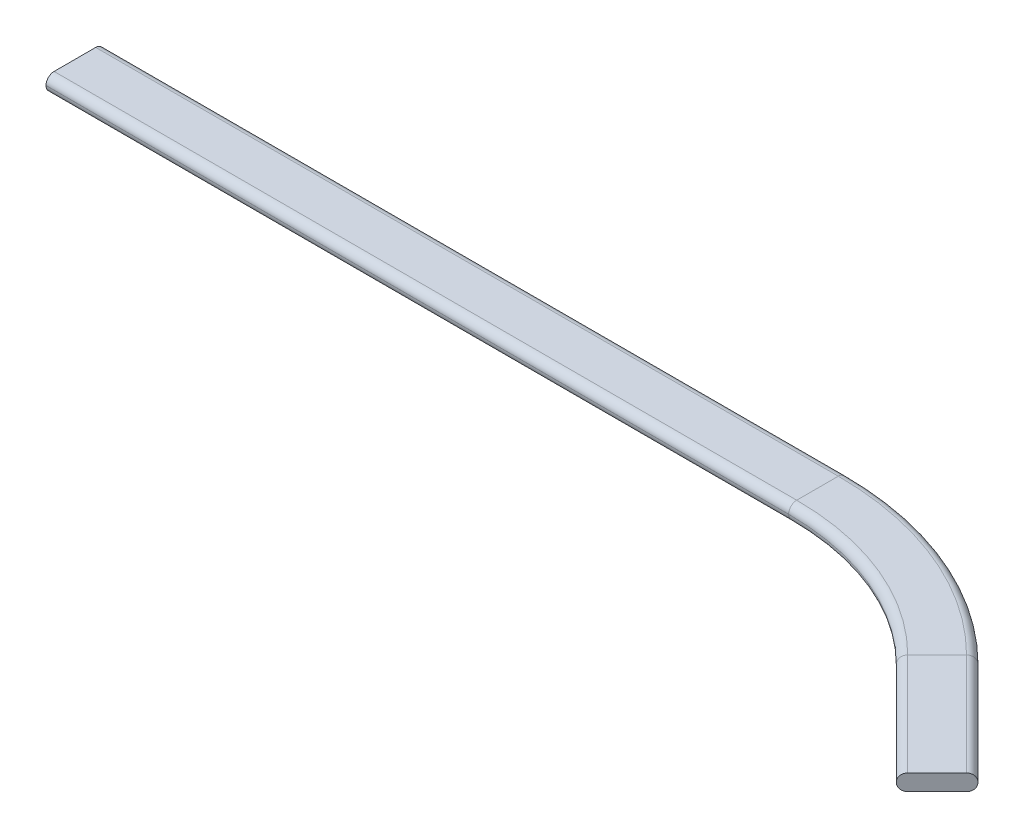
SolidWorks part; units mm, degrees
ref_plane "Front Plane" through (0, 0, 0) normal (0, 0, 1) x (1, 0, 0)
ref_plane "Top Plane" through (0, 0, 0) normal (0, 1, 0) x (1, 0, 0)
ref_plane "Right Plane" through (0, 0, 0) normal (1, 0, 0) x (0, 0, -1)
sketch "Sketch1" plane through (0, 0, 0) normal (0, 1, 0) x (1, 0, 0)
  line L0 (0, 0) -> (90, 0)
  line L1 (114.7487, -10.2513) -> (127.1309, -22.6335)
  arc A0 (90, 0) -> (114.7487, -10.2513) centre (90, -35) cw
  point P5 (99.1421, -5.8579)
  point P6 (120.5258, -26.5325)
  dimension "D1" = 35
  dimension "D3" = 135
  dimension "D2" = 90
  dimension "D4" = 45
ref_plane "Plane1" through (0, 0, 0) normal (1, 0, 0) x (0, 0, -1)
sketch "Sketch3" plane through (0, 0, 0) normal (1, 0, 0) x (0, 0, -1)
  line L1 (3.5, -0.985) -> (-3.5, -0.985)
  line L2 (3.5, -0.985) -> (3.5, 0.985)
  line L3 (3.5, 0.985) -> (-3.5, 0.985)
  line L4 (-3.5, -0.985) -> (-3.5, 0.985)
  line L5 (3.5, -0.985) -> (-3.5, 0.985) construction
  line L6 (3.5, 0.985) -> (-3.5, -0.985) construction
  point P0 (0, 0)
  dimension "D1" = 7
  dimension "D2" = 1.97
sweep "Sweep1" add profiles "Sketch3" path "Sketch1"
fillet "Fillet1" radius 0.98 12 edges at (118.465, -0.985, 18.9172) (102.0545, -0.985, 5.8978) (118.465, 0.985, 18.9172) (102.0545, 0.985, 5.8978) (123.4147, -0.985, 13.9675) (104.7333, -0.985, -0.5694) (123.4147, 0.985, 13.9675) (104.7333, 0.985, -0.5694) (45, -0.985, 3.5) (45, 0.985, 3.5) (45, -0.985, -3.5) (45, 0.985, -3.5)
ref_plane "Plane2" through (0, 0, 0.3) normal (0, 0, 1) x (1, 0, 0)
sketch "Sketch7" plane through (0, 0, 0.3) normal (0, 0, 1) x (1, 0, 0)
  line L4 (1.4873, -0.995) -> (0, -0.995)
  line L5 (0.302, -1.8935) -> (1.4873, -0.995)
  circle A2 centre (0, -1.495) radius 0.25
  arc A3 (0.302, -1.8935) -> (0, -0.995) centre (0, -1.495) cw
  dimension "D1" = 0.5
  dimension "D2" = 0.5
  dimension "D3" = 0.302
  dimension "D4" = 0.995
extrude "Boss-Extrude1" add sketch "Sketch7" against normal blind 0.6 separate body
